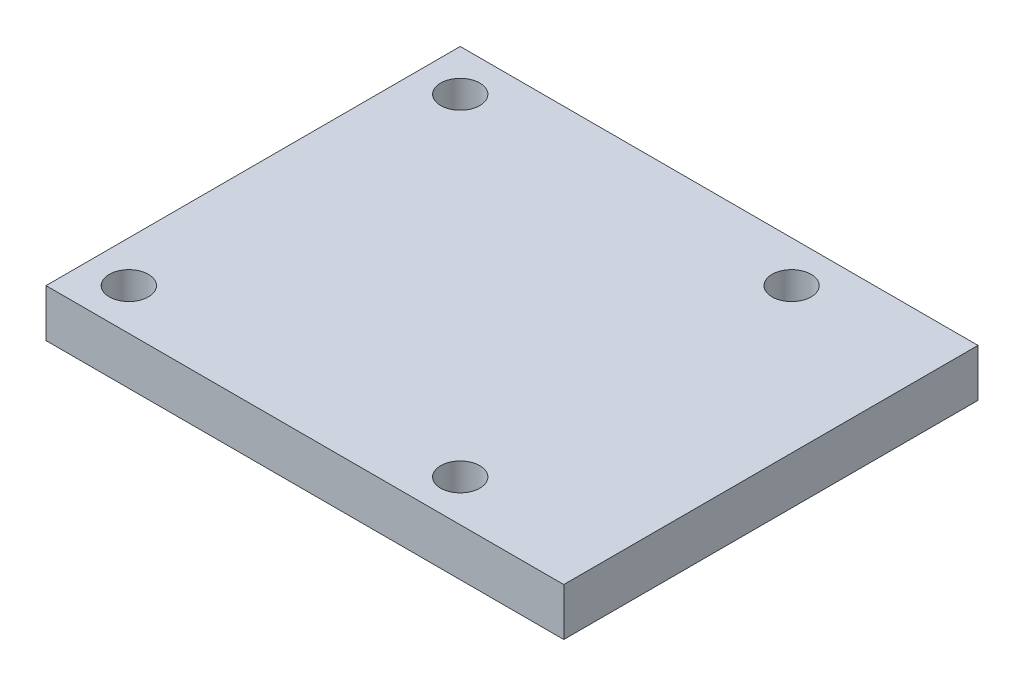
SolidWorks part; units mm, degrees
ref_plane "Front Plane" through (0, 0, 0) normal (0, 0, 1) x (1, 0, 0)
ref_plane "Top Plane" through (0, 0, 0) normal (0, 1, 0) x (1, 0, 0)
ref_plane "Right Plane" through (0, 0, 0) normal (1, 0, 0) x (0, 0, -1)
sketch "Sketch1" plane through (0, 0, 0) normal (0, 1, 0) x (1, 0, 0)
  line L1 (-15.875, -12.7) -> (15.875, -12.7)
  line L2 (-15.875, -12.7) -> (-15.875, 12.7)
  line L3 (-15.875, 12.7) -> (15.875, 12.7)
  line L4 (15.875, -12.7) -> (15.875, 12.7)
  line L5 (-15.875, -12.7) -> (15.875, 12.7) construction
  line L6 (-15.875, 12.7) -> (15.875, -12.7) construction
  point P0 (0, 0)
  dimension "D1" = 31.75
  dimension "D2" = 25.4
extrude "Boss-Extrude1" add sketch "Sketch1" along normal blind 2.921
sketch "Sketch2" plane through (0, 2.921, 0) normal (0, 1, 0) x (1, 0, 0)
  line L2 (15.875, 12.7) -> (-15.875, 12.7) construction
  line L3 (-15.875, 12.7) -> (-15.875, -12.7) construction
  line L4 (-15.875, -12.7) -> (15.875, -12.7) construction
  point P4 (6.985, 10.16)
  point P5 (6.985, -10.16)
  point P6 (-13.335, -10.16)
  point P7 (-13.335, 10.16)
  point P10 (0, 0)
  point P11 (0, 0)
  point P12 (0, 0)
  point P13 (0, 0)
  point P14 (0, 0)
  dimension "D1" = 2.54
  dimension "D2" = 2.54
  dimension "D3" = 2.54
  dimension "D4" = 2.54
  dimension "D5" = 22.86
hole_wizard "M2 Clearance Hole1" positions "Sketch3" profile "Sketch4" hole size "M2" standard "ANSI Metric" end condition through all
sketch "Sketch3" plane through (0, 2.921, 0) normal (0, 1, 0) x (1, 0, 0)
  point P0 (-13.335, 10.16)
  point P3 (6.985, 10.16)
  point P6 (6.985, -10.16)
  point P9 (-13.335, -10.16)
sketch "Sketch4" plane through (-13.335, 2.921, -10.16) normal (1, 0, 0) x (0, 0, 1)
  line L0 (0, 0) -> (0, 2.921)
  line L1 (0, 2.921) -> (1.2, 2.921)
  line L2 (1.2, 2.921) -> (1.2, 0)
  line L5 (1.2, 0) -> (0, 0)
  line L11 (0, -6.35) -> (0, 107.95) construction
  dimension "Thru Hole Dia." = 2.4
  dimension "Thru Hole Depth" = 2.921
